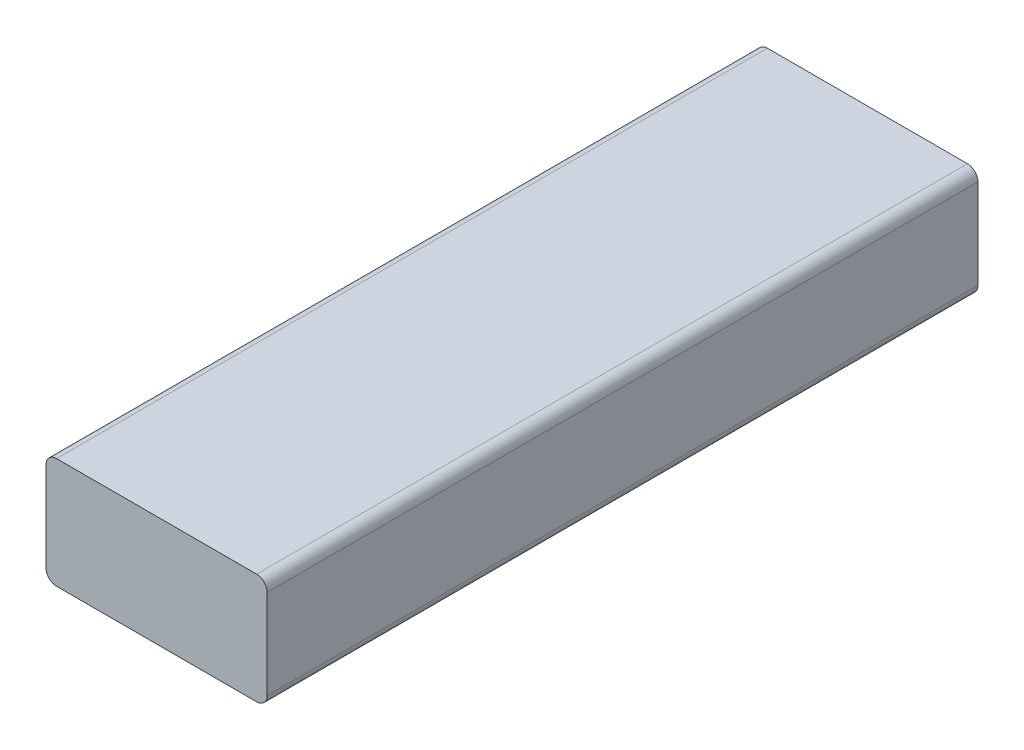
SolidWorks part; units mm, degrees
ref_plane "前视基准面" through (0, 0, 0) normal (0, 0, 1) x (1, 0, 0)
ref_plane "上视基准面" through (0, 0, 0) normal (0, 1, 0) x (1, 0, 0)
ref_plane "右视基准面" through (0, 0, 0) normal (1, 0, 0) x (0, 0, -1)
other "Configuration Table"
sketch "Sketch1" plane through (0, 0, 0) normal (0, 1, 0) x (1, 0, 0)
  line L1 (-26.0432, 112.0091) -> (15.9568, 112.0091)
  line L2 (-26.0432, 112.0091) -> (-26.0432, -22.9909)
  line L3 (-26.0432, -22.9909) -> (15.9568, -22.9909)
  line L4 (15.9568, 112.0091) -> (15.9568, -22.9909)
  dimension "D1" = 42
  dimension "D2" = 135
extrude "Boss-Extrude1" add sketch "Sketch1" along normal blind 21 contours L2 L3 L4 L1
fillet "Fillet1" radius 2 4 edges at (-26.0432, 0, -44.5091) (15.9568, 0, -44.5091) (15.9568, 21, -44.5091) (-26.0432, 21, -44.5091)
sketch "Sketch3" plane through (0, 21, 0) normal (0, 1, 0) x (1, 0, 0)
  line L0 (-5.0432, 112.0091) -> (-5.0432, -22.9909) construction
  line L1 (-24.0432, 112.0091) -> (13.9568, 112.0091) construction
  line L2 (-24.0432, -22.9909) -> (13.9568, -22.9909) construction
  line L3 (-24.0432, 44.5091) -> (13.9568, 44.5091) construction
  line L4 (-24.0432, 112.0091) -> (-24.0432, -22.9909) construction
  line L5 (13.9568, -22.9909) -> (13.9568, 112.0091) construction
